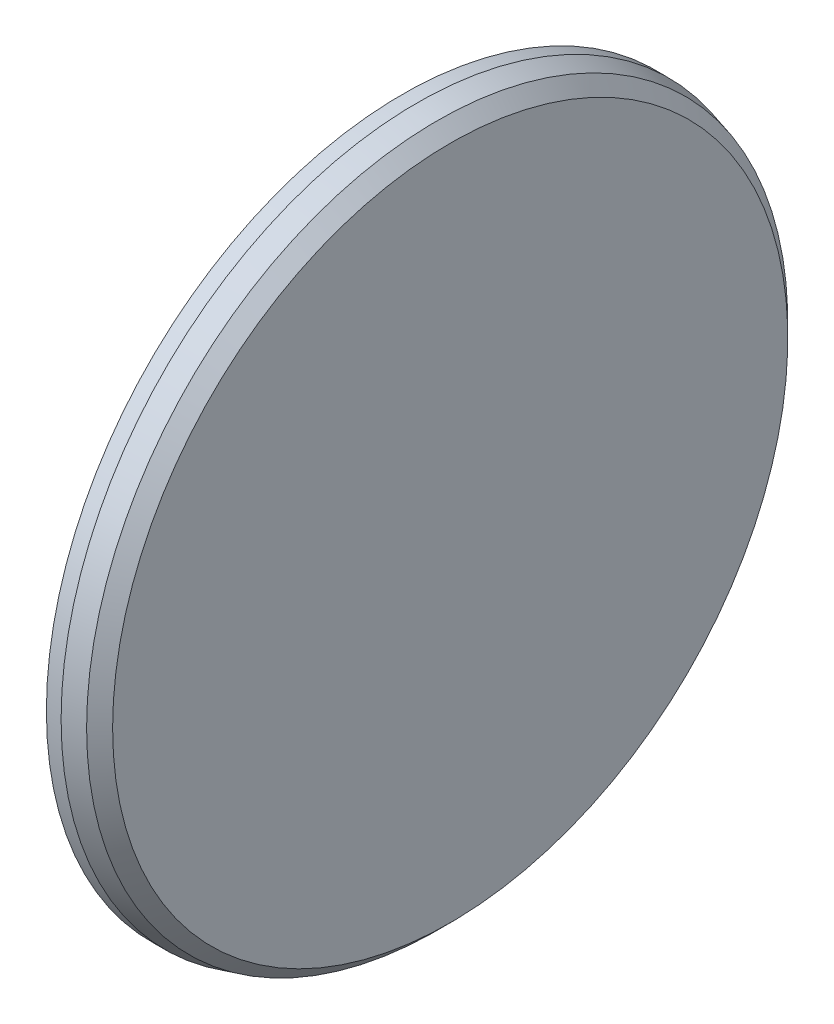
SolidWorks part; units mm, degrees
material "1060 合金"
ref_plane "前视基准面" through (0, 0, 0) normal (0, 0, 1) x (1, 0, 0)
ref_plane "上视基准面" through (0, 0, 0) normal (0, 1, 0) x (1, 0, 0)
ref_plane "右视基准面" through (0, 0, 0) normal (1, 0, 0) x (0, 0, -1)
sketch "草图1" plane through (0, 0, 0) normal (0, 0, 1) x (1, 0, 0)
  line L0 (0, 496.3951) -> (0, -545.0195) construction
  line L1 (-619.2979, 0) -> (691.2767, 0) construction
  line L2 (0, 0) -> (0, 458.75)
  line L3 (0, 458.75) -> (-17.6795, 476.4295)
  line L4 (-17.6795, 476.4295) -> (-45, 483.75)
  line L5 (-45, 483.75) -> (-65, 483.75)
  line L6 (-65, 483.75) -> (-65, 438.75)
  line L7 (-65, 438.75) -> (-30, 438.75)
  line L8 (-30, 438.75) -> (-30, 100)
  line L9 (-30, 100) -> (-85, 100)
  line L10 (-85, 100) -> (-85, 0)
  line L11 (-85, 0) -> (0, 0)
  dimension "D1" = 967.5
  dimension "D2" = 30
  dimension "D3" = 917.5
  dimension "D4" = 65
  dimension "D5" = 200
  dimension "D6" = 85
  dimension "D7" = 20
  dimension "D8" = 15
  dimension "D9" = 45
  dimension "D10" = 45
revolve "旋转1" add sketch "草图1" angle 360 about L1
sketch "草图3" plane through (-30, 0, 0) normal (-1, 0, 0) x (0, 0, 1)
  line L0 (0, 709.231) -> (0, -770.794) construction
  line L1 (-20, 438.2939) -> (-20, 97.9796)
  line L2 (20, 438.2939) -> (20, 97.9796)
  circle A0 centre (0, 0) radius 100 construction
  circle A1 centre (0, 0) radius 438.75
  circle A2 centre (0, 0) radius 438.75
  circle A3 centre (0, 0) radius 100
  circle A4 centre (0, 0) radius 100 construction
  circle A5 centre (0, 0) radius 438.75 construction
  dimension "D2" = 40
  dimension "D1" = 0
extrude "凸台-拉伸1" add sketch "草图3" along normal offset from surface (25 mm away) 10 contours L0 A2 L1 A0 | A1 L0 A3 L2
fillet "圆角3" radius 60 1 edges at (-42.5, 438.2939, -20)
fillet "圆角4" radius 10 3 edges at (-42.5, 97.9796, -20) (-42.5, 97.9796, 20) (-42.5, 438.2939, 20)
pattern_circular "阵列(圆周)1" count 9 every 40 about axis through (0, 0, 0) along (1, 0, 0) of "凸台-拉伸1", "圆角3", "圆角4"
